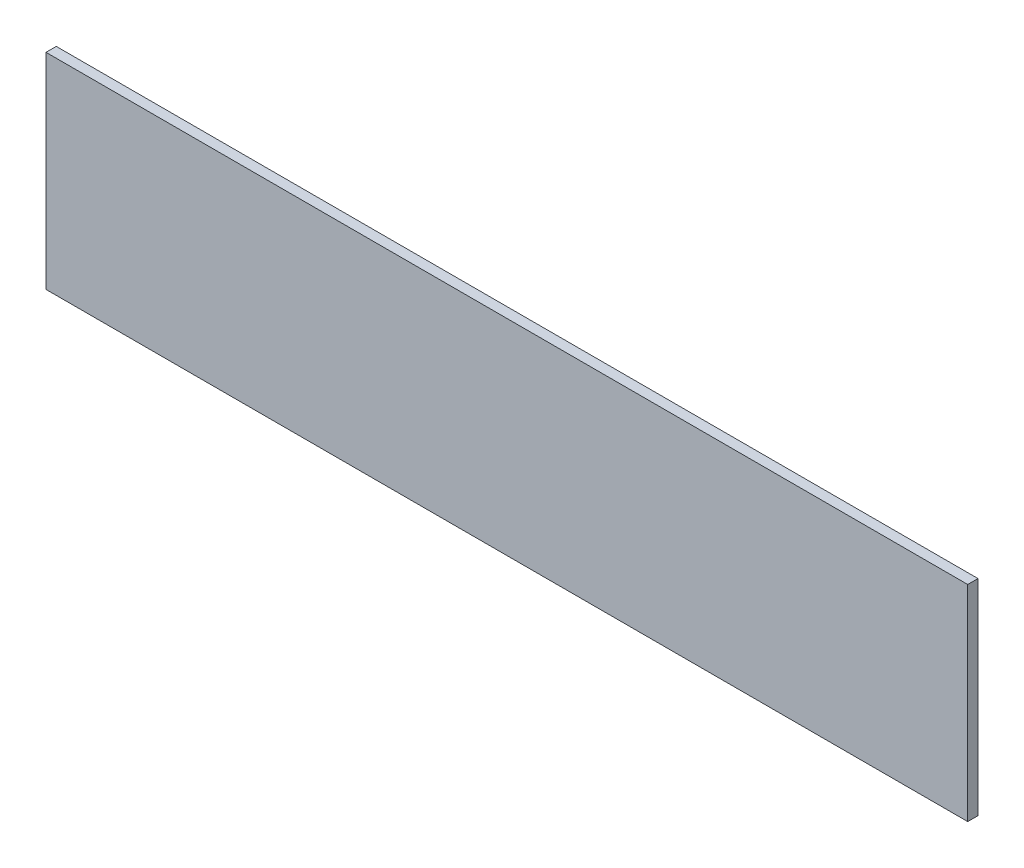
SolidWorks part; units mm, degrees
ref_plane "Plan de face" through (0, 0, 0) normal (0, 0, 1) x (1, 0, 0)
ref_plane "Plan de dessus" through (0, 0, 0) normal (0, 1, 0) x (1, 0, 0)
ref_plane "Plan de droite" through (0, 0, 0) normal (1, 0, 0) x (0, 0, -1)
sketch "Esquisse1" plane through (0, 0, 0) normal (0, 0, 1) x (1, 0, 0)
  line L1 (-285, 63.5) -> (285, 63.5)
  line L2 (-285, 63.5) -> (-285, -63.5)
  line L3 (-285, -63.5) -> (285, -63.5)
  line L4 (285, 63.5) -> (285, -63.5)
  point P4 (0, 63.5)
  point P6 (-285, 0)
  dimension "D1" = 570
  dimension "D2" = 127
extrude "Boss.-Extru.1" add sketch "Esquisse1" along normal mid plane 6.35
